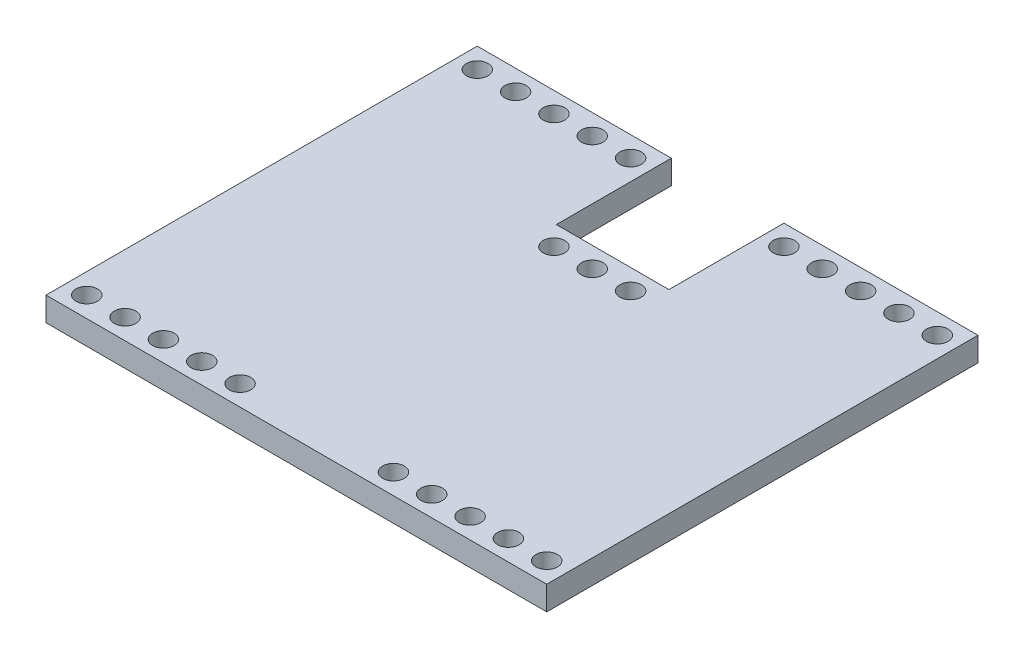
SolidWorks part; units mm, degrees
ref_plane "前视基准面" through (0, 0, 0) normal (0, 0, 1) x (1, 0, 0)
ref_plane "上视基准面" through (0, 0, 0) normal (0, 1, 0) x (1, 0, 0)
ref_plane "右视基准面" through (0, 0, 0) normal (1, 0, 0) x (0, 0, -1)
sketch "草图2" plane through (0, 0, 0) normal (0, 1, 0) x (1, 0, 0)
  line L0 (-48, 40.75) -> (-40, 40.75) construction
  line L1 (-52.25, 45) -> (52.25, 45)
  line L2 (-52.25, 45) -> (-52.25, -45)
  line L3 (-52.25, -45) -> (52.25, -45)
  line L4 (52.25, 45) -> (52.25, -45)
  line L5 (-52.25, 45) -> (52.25, -45) construction
  line L6 (-52.25, -45) -> (52.25, 45) construction
  line L7 (0, 45) -> (0, -45) construction
  line L8 (-52.25, 0) -> (52.25, 0) construction
  line L9 (-11.75, 21) -> (11.75, 21)
  line L10 (-11.75, 21) -> (-11.75, 45)
  line L11 (-11.75, 45) -> (11.75, 45)
  line L12 (11.75, 21) -> (11.75, 45)
  line L13 (-11.75, 21) -> (11.75, 45) construction
  line L14 (-11.75, 45) -> (11.75, 21) construction
  circle A0 centre (-48, 40.75) radius 2.25
  circle A1 centre (-40, 40.75) radius 2.25
  circle A2 centre (-32, 40.75) radius 2.25
  circle A3 centre (-24, 40.75) radius 2.25
  circle A4 centre (-16, 40.75) radius 2.25
  circle A5 centre (48, 40.75) radius 2.25
  circle A6 centre (40, 40.75) radius 2.25
  circle A7 centre (32, 40.75) radius 2.25
  circle A8 centre (24, 40.75) radius 2.25
  circle A9 centre (16, 40.75) radius 2.25
  circle A10 centre (-8, 16.75) radius 2.25
  circle A11 centre (0, 16.75) radius 2.25
  circle A13 centre (8, 16.75) radius 2.25
  circle A14 centre (48, -40.75) radius 2.25
  circle A15 centre (40, -40.75) radius 2.25
  circle A16 centre (32, -40.75) radius 2.25
  circle A17 centre (24, -40.75) radius 2.25
  circle A18 centre (16, -40.75) radius 2.25
  circle A19 centre (-16, -40.75) radius 2.25
  circle A20 centre (-24, -40.75) radius 2.25
  circle A21 centre (-32, -40.75) radius 2.25
  circle A22 centre (-40, -40.75) radius 2.25
  circle A23 centre (-48, -40.75) radius 2.25
  point P0 (0, 0)
  point P20 (0, 33)
  point P44 (0, 0)
  dimension "D3" = 4.5
  dimension "D4" = 4.25
  dimension "D10" = 4.5
  dimension "D11" = 24
  dimension "D12" = 4.5
  dimension "D13" = 8
  dimension "D1" = 104.5
  dimension "D2" = 90
  dimension "D5" = 4.25
  dimension "D7" = 8
  dimension "D8" = 4.25
  dimension "D9" = 4.25
  dimension "D6" = 5
extrude "凸台-拉伸1" add sketch "草图2" along normal blind 5 contours L12 L9 L10 L1 L2 L3 L4 A8 A6 A0 A1 A2 A3 A4 A5 A7 A9
